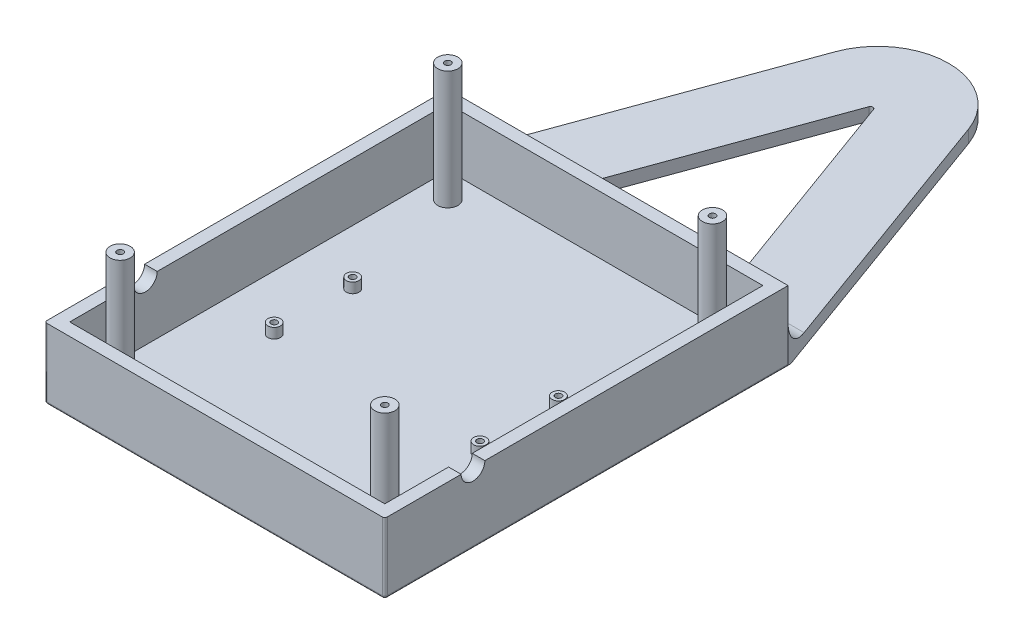
SolidWorks part; units mm, degrees
ref_plane "Front Plane" through (0, 0, 0) normal (0, 0, 1) x (1, 0, 0)
ref_plane "Top Plane" through (0, 0, 0) normal (0, 1, 0) x (1, 0, 0)
ref_plane "Right Plane" through (0, 0, 0) normal (1, 0, 0) x (0, 0, -1)
sketch "Sketch1" plane through (0, 0, 0) normal (0, 1, 0) x (1, 0, 0)
  line L0 (-37.5, 80) -> (37.5, 80)
  line L2 (-67.5, 80) -> (-67.5, -80)
  line L3 (-67.5, -80) -> (67.5, -80)
  line L4 (67.5, 80) -> (67.5, -80)
  line L5 (-67.5, 80) -> (67.5, -80) construction
  line L6 (-67.5, -80) -> (67.5, 80) construction
  line L7 (-37.5, 80) -> (0, 183.0304)
  line L8 (0, 183.0304) -> (37.5, 80)
  line L9 (26.4907, 192.6722) -> (67.5, 80)
  line L11 (-67.5, 80) -> (-26.4907, 192.6722)
  arc A0 (-26.4907, 192.6722) -> (26.4907, 192.6722) centre (0, 183.0304) cw
  point P0 (0, 0)
  dimension "D5" = 70
  dimension "D1" = 135
  dimension "D2" = 160
  dimension "D3" = 30
  dimension "D4" = 30
  dimension "D6" = 70
  dimension "D7" = 70
  dimension "D8" = 70
  dimension "D9" = 160
extrude "Boss-Extrude1" add sketch "Sketch1" along normal blind 5
sketch "Sketch2" plane through (0, 5, 0) normal (0, 1, 0) x (1, 0, 0)
  line L0 (-67.5, 80) -> (67.5, 80)
  line L1 (67.5, 80) -> (67.5, -80)
  line L2 (67.5, -80) -> (-67.5, -80)
  line L3 (-67.5, -80) -> (-67.5, 80)
  line L5 (-62.5, 75) -> (62.5, 75)
  line L6 (-62.5, 75) -> (-62.5, -75)
  line L7 (-62.5, -75) -> (62.5, -75)
  line L8 (62.5, 75) -> (62.5, -75)
  line L9 (-62.5, 75) -> (62.5, -75) construction
  line L10 (-62.5, -75) -> (62.5, 75) construction
  point P4 (0, 0)
  dimension "D1" = 5
  dimension "D2" = 5
extrude "Boss-Extrude2" add sketch "Sketch2" along normal blind 23
sketch "Sketch3" plane through (67.5, 0, 0) normal (1, 0, 0) x (0, 0, -1)
  line L0 (-80, 28) -> (80, 28) construction
  line L1 (-80, 28) -> (-80, 0) construction
  circle A0 centre (-45, 28) radius 4.7
  dimension "D1" = 9.4
  dimension "D2" = 35
extrude "Cut-Extrude1" cut sketch "Sketch3" against normal blind 140
sketch "Sketch4" plane through (0, 5, 0) normal (0, 1, 0) x (1, 0, 0)
  line L0 (-67.5, 80) -> (-67.5, -40.3) construction
  line L1 (67.5, 80) -> (-67.5, 80) construction
  line L2 (-96.3854, 0) -> (128.0427, 0) construction
  line L3 (0, 90.1258) -> (0, -70.7049) construction
  circle A0 centre (-52.5, 65) radius 4
  circle A1 centre (52.5, 65) radius 4
  circle A2 centre (52.5, -65) radius 4
  circle A3 centre (-52.5, -65) radius 4
  dimension "D3" = 8
  dimension "D1" = 15
  dimension "D2" = 15
extrude "Boss-Extrude3" add sketch "Sketch4" along normal blind 47
hole_wizard "Ø2.5mm Dowel Hole1" positions "Sketch5" profile "Sketch6" hole size "Ø2.5" standard "ISO"
sketch "Sketch5" plane through (0, 52, 0) normal (0, 1, 0) x (1, 0, 0)
  point P0 (-52.5, 65)
  point P3 (52.5, 65)
  point P6 (52.5, -65)
  point P9 (-52.5, -45)
  point P10 (-52.5, -65)
sketch "Sketch6" plane through (-52.5, 52, -65) normal (1, 0, 0) x (0, 0, 1)
  line L0 (0, 0) -> (0, 12.7511)
  line L1 (0, 12.7511) -> (1.25, 12)
  line L2 (1.25, 12) -> (1.25, 0)
  line L5 (1.25, 0) -> (0, 0)
  line L10 (0, 12.7511) -> (-1.25, 12) construction
  line L11 (0, -6.35) -> (0, 107.95) construction
  dimension "Hole Dia." = 2.5
  dimension "Hole Depth" = 12
  dimension "Drill Angle" = 118
fillet "Fillet1" radius 1 6 edges at (-67.5, 0, 0) (-67.5, 14, 80) (0, 0, 80) (67.5, 14, 80) (67.5, 0, 0) (0, 2.5, -183.0304)
sketch "Sketch8" plane through (0, 5, 0) normal (0, 1, 0) x (1, 0, 0)
  line L0 (-108.3758, 0) -> (96.7482, 0) construction
  line L1 (0, 89.3182) -> (0, -71.7163) construction
  circle A0 centre (-40.82, 15.565) radius 2.5
  circle A1 centre (-40.82, -15.565) radius 2.5
  circle A2 centre (40.82, -15.565) radius 2.5
  circle A3 centre (40.82, 15.565) radius 2.5
  dimension "D1" = 5
  dimension "D2" = 15.565
  dimension "D3" = 40.82
extrude "Boss-Extrude4" add sketch "Sketch8" along normal blind 4
hole_wizard "Ø2.5 (2.5) Diameter Hole2" positions "Sketch11" profile "Sketch12" hole size "Ø2.5" standard "ISO"
sketch "Sketch11" plane through (0, 9, 0) normal (0, 1, 0) x (1, 0, 0)
  point P0 (-40.82, 15.565)
  point P3 (-40.82, -15.565)
  point P6 (40.82, -15.565)
  point P9 (40.82, 15.565)
sketch "Sketch12" plane through (-40.82, 9, -15.565) normal (1, 0, 0) x (0, 0, 1)
  line L0 (0, 0) -> (0, 5.7511)
  line L1 (0, 5.7511) -> (1.25, 5)
  line L2 (1.25, 5) -> (1.25, 0)
  line L5 (1.25, 0) -> (0, 0)
  line L10 (0, 5.7511) -> (-1.25, 5) construction
  line L11 (0, -6.35) -> (0, 107.95) construction
  dimension "Hole Dia." = 2.5
  dimension "Hole Depth" = 5
  dimension "Drill Angle" = 118
fillet "Fillet2" radius 10 2 edges at (-52.5, 5, -80) (52.5, 5, -80)
